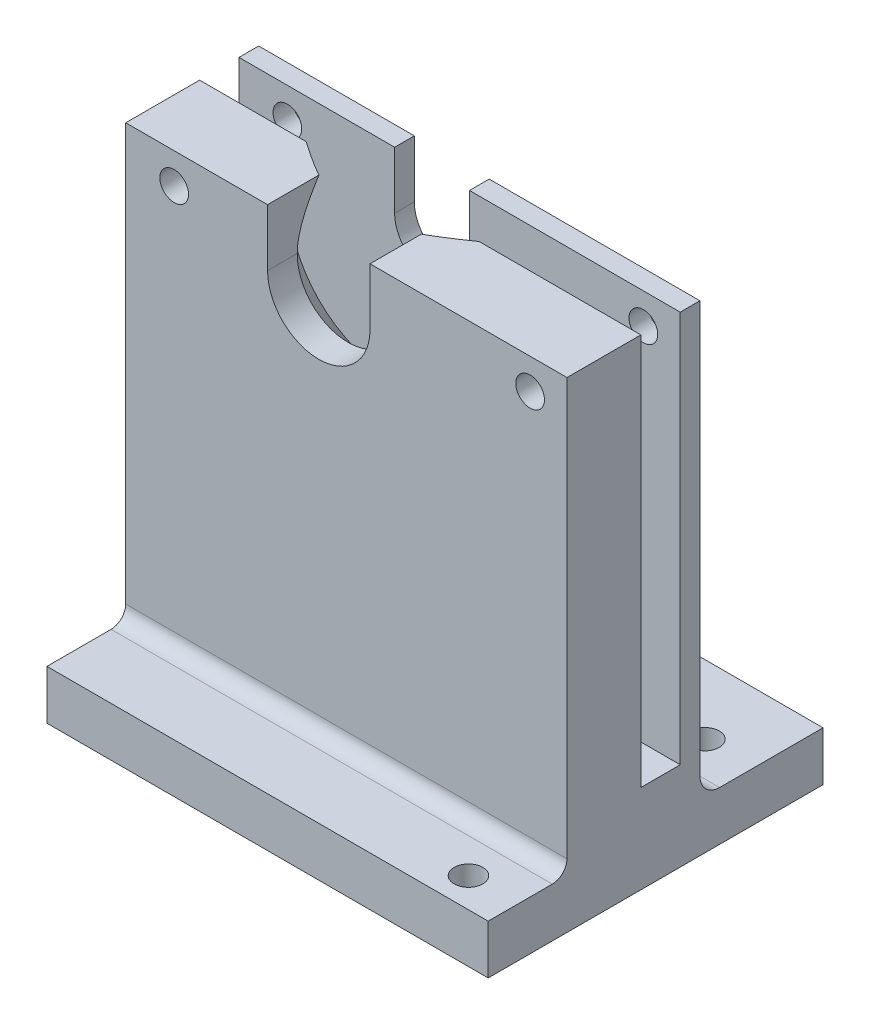
SolidWorks part; units mm, degrees
ref_plane "Front Plane" through (0, 0, 0) normal (0, 0, 1) x (1, 0, 0)
ref_plane "Top Plane" through (0, 0, 0) normal (0, 1, 0) x (1, 0, 0)
ref_plane "Right Plane" through (0, 0, 0) normal (1, 0, 0) x (0, 0, -1)
sketch "Sketch1" plane through (0, 0, 0) normal (0, 1, 0) x (1, 0, 0)
  line L0 (-40.9657, 0) -> (60.4955, 0) construction
  line L1 (0, -25.8126) -> (0, 33.2082) construction
  line L3 (-19.05, 4.7625) -> (37.846, 4.7625)
  line L4 (-19.05, 4.7625) -> (-19.05, -4.7625)
  line L5 (-19.05, -4.7625) -> (37.846, -4.7625)
  line L6 (37.846, 4.7625) -> (37.846, -4.7625)
  dimension "D1" = 19.05
  dimension "D2" = 56.896
  dimension "D3" = 4.7625
  dimension "D4" = 9.525
extrude "Boss-Extrude1" add sketch "Sketch1" along normal blind 61.976
sketch "Sketch2" plane through (0, 0, -4.7625) normal (0, 0, -1) x (-1, 0, 0)
  line L1 (-37.846, 61.976) -> (-37.846, 0) construction
  line L2 (-37.846, 0) -> (19.05, 0) construction
  circle A0 centre (-5.842, 54.5521) radius 13.3985
  dimension "D1" = 32.004
  dimension "D3" = 26.797
  dimension "D2" = 54.5521
extrude "Cut-Extrude1" cut sketch "Sketch2" against normal blind 5.8801 draft 50
sketch "Sketch5" plane through (0, 0, -4.7625) normal (0, 0, -1) x (-1, 0, 0)
  line L0 (19.05, 61.976) -> (19.05, 0) construction
  line L1 (-37.846, 0) -> (19.05, 0)
  line L2 (-37.846, 0) -> (-37.846, 11.43)
  line L3 (-37.846, 11.43) -> (19.05, 11.43)
  line L4 (19.05, 0) -> (19.05, 11.43)
  dimension "D1" = 11.43
extrude "Boss-Extrude2" add sketch "Sketch5" along normal blind 7.62
sketch "Sketch6" plane through (0, 11.43, 0) normal (0, 1, 0) x (1, 0, 0)
  line L0 (-19.05, 12.3825) -> (-19.05, 4.7625) construction
  line L1 (37.846, 12.3825) -> (-19.05, 12.3825)
  line L2 (37.846, 12.3825) -> (37.846, 9.8425)
  line L3 (37.846, 9.8425) -> (-19.05, 9.8425)
  line L4 (-19.05, 12.3825) -> (-19.05, 9.8425)
  line L5 (-19.05, 4.7625) -> (37.846, 4.7625) construction
  dimension "D1" = 5.08
sketch "Sketch16" plane through (0, 11.43, 0) normal (0, 1, 0) x (1, 0, 0)
  line L0 (37.846, 12.3825) -> (37.846, 4.7625) construction
  line L1 (19.2405, 4.7625) -> (-7.5565, 4.7625) construction
  circle A0 centre (31.496, 7.3025) radius 1.2818
  dimension "D1" = 6.35
  dimension "D2" = 2.54
hole_wizard "Tap Drill for M3x0.5 Tap3" positions "Sketch17" profile "Sketch18" hole size "M3x0.5" standard "ANSI Metric"
sketch "Sketch17" plane through (0, 11.43, 0) normal (0, 1, 0) x (1, 0, 0)
  point P0 (31.496, 7.3025)
sketch "Sketch18" plane through (31.496, 11.43, -7.3025) normal (1, 0, 0) x (0, 0, 1)
  line L0 (0, 0) -> (0, 26.1511)
  line L1 (0, 26.1511) -> (1.25, 25.4)
  line L2 (1.25, 25.4) -> (1.25, 0)
  line L5 (1.25, 0) -> (0, 0)
  line L10 (0, 26.1511) -> (-1.25, 25.4) construction
  line L11 (0, -6.35) -> (0, 107.95) construction
  dimension "Hole Dia." = 2.5
  dimension "Hole Depth" = 25.4
  dimension "Drill Angle" = 118
sketch "Sketch19" plane through (37.846, 0, 0) normal (1, 0, 0) x (0, 0, -1)
  line L0 (4.7625, 61.976) -> (4.7625, 11.43) construction
  line L1 (12.3825, 0) -> (28.2575, 0)
  line L2 (12.3825, 0) -> (12.3825, 8.89)
  line L3 (14.9225, 6.35) -> (28.2575, 6.35)
  line L4 (28.2575, 0) -> (28.2575, 6.35)
  line L5 (-4.7625, 61.976) -> (-4.7625, 0) construction
  line L8 (-4.7625, 0) -> (-14.9225, 0)
  line L9 (-4.7625, 0) -> (-4.7625, 8.2423)
  line L10 (-6.6548, 6.35) -> (-14.9225, 6.35)
  line L11 (-14.9225, 0) -> (-14.9225, 6.35)
  line L12 (3.81, 0) -> (3.81, 9.1206) construction
  line L13 (-4.7625, 0) -> (12.3825, 0) construction
  arc A0 (12.3825, 8.89) -> (14.9225, 6.35) centre (14.9225, 8.89) ccw
  arc A1 (-6.6548, 6.35) -> (-4.7625, 8.2423) centre (-6.6548, 8.2423) ccw
  dimension "D2" = 8.89
  dimension "D3" = 10.16
  dimension "D5" = 1.8923
  dimension "D6" = 6.35
  dimension "D4" = 2.54
  dimension "D1" = 43.18
  dimension "D7" = 7.62
extrude "Boss-Extrude4" add sketch "Sketch19" against normal up to surface (56.896 mm away) up to face at (-19.05, 24.4687, -4.1275)
sketch "Sketch20" plane through (0, 0, 0) normal (0, -1, 0) x (1, 0, 0)
  line L0 (37.846, 14.9225) -> (37.846, -28.2575) construction
  line L1 (-19.05, 14.9225) -> (37.846, 14.9225) construction
  circle A0 centre (31.496, -19.3675) radius 1.778
  circle A1 centre (31.496, 11.1125) radius 1.778
  dimension "D1" = 6.35
  dimension "D2" = 3.81
  dimension "D3" = 6.35
  dimension "D5" = 3.556
  dimension "D4" = 30.48
hole_wizard "M3 Clearance Hole3" positions "Sketch21" profile "Sketch22" hole size "M3" standard "ANSI Metric"
sketch "Sketch21" plane through (0, 0, 0) normal (0, -1, 0) x (-1, 0, 0)
  point P0 (-31.496, -11.1125)
  point P3 (-31.496, 19.3675)
sketch "Sketch22" plane through (31.496, 0, 11.1125) normal (1, 0, 0) x (0, 0, -1)
  line L0 (0, 0) -> (0, 26.5116)
  line L1 (0, 26.5116) -> (1.85, 25.4)
  line L2 (1.85, 25.4) -> (1.85, 0)
  line L5 (1.85, 0) -> (0, 0)
  line L10 (0, 26.5116) -> (-1.85, 25.4) construction
  line L11 (0, -6.35) -> (0, 107.95) construction
  dimension "Hole Dia." = 3.7
  dimension "Hole Depth" = 25.4
  dimension "Drill Angle" = 118
extrude "Boss-Extrude5" add sketch "Sketch6" along normal up to surface (50.546 mm away) up to face at (8.0344, 61.976, -0.7627)
sketch "Sketch24" plane through (0, 0, -12.3825) normal (0, 0, -1) x (-1, 0, 0)
  line L0 (-37.846, 61.976) -> (-37.846, 8.89) construction
  line L1 (19.05, 0) -> (-37.846, 0) construction
  line L2 (-1.016, 54.61) -> (-1.016, 61.976)
  line L3 (-37.846, 61.976) -> (19.05, 61.976) construction
  line L4 (-10.668, 54.61) -> (-10.668, 61.976)
  circle A0 centre (-5.842, 54.61) radius 4.826
  line M3 (19.05, 61.976) -> (-37.846, 61.976)
  dimension "D1" = 32.004
  dimension "D3" = 9.652
  dimension "D2" = 54.61
extrude "Cut-Extrude2" cut sketch "Sketch24" against normal blind 2.54 contours A0 L2 L4 M3 | A0
sketch "Sketch25" plane through (0, 0, 4.7625) normal (0, 0, 1) x (1, 0, 0)
  line L0 (37.846, 61.976) -> (37.846, 8.2423) construction
  line L1 (-19.05, 0) -> (37.846, 0) construction
  line L2 (12.446, 54.61) -> (12.446, 61.976)
  line L3 (-19.05, 61.976) -> (37.846, 61.976) construction
  line L4 (-0.762, 54.61) -> (-0.762, 61.976)
  circle A0 centre (5.842, 54.61) radius 6.604
  line M4 (37.846, 61.976) -> (-19.05, 61.976)
  dimension "D1" = 32.004
  dimension "D3" = 13.208
  dimension "D2" = 54.61
extrude "Cut-Extrude3" cut sketch "Sketch25" against normal blind 7.366 contours A0 L2 L4 M4 | A0
hole_wizard "M3 Clearance Hole4" positions "Sketch26" profile "Sketch27" hole size "M3" standard "ANSI Metric"
sketch "Sketch26" plane through (0, 0, -12.3825) normal (0, 0, -1) x (-1, 0, 0)
  point P0 (-33.0907, 58.0299)
  point P2 (12.8061, 58.0299)
sketch "Sketch27" plane through (33.0907, 58.0299, -12.3825) normal (1, 0, 0) x (0, 1, 0)
  line L0 (0, 0) -> (0, 18.3836)
  line L1 (0, 18.3836) -> (1.85, 17.272)
  line L2 (1.85, 17.272) -> (1.85, 0)
  line L5 (1.85, 0) -> (0, 0)
  line L10 (0, 18.3836) -> (-1.85, 17.272) construction
  line L11 (0, -6.35) -> (0, 107.95) construction
  dimension "Hole Dia." = 3.7
  dimension "Hole Depth" = 17.272
  dimension "Drill Angle" = 118
